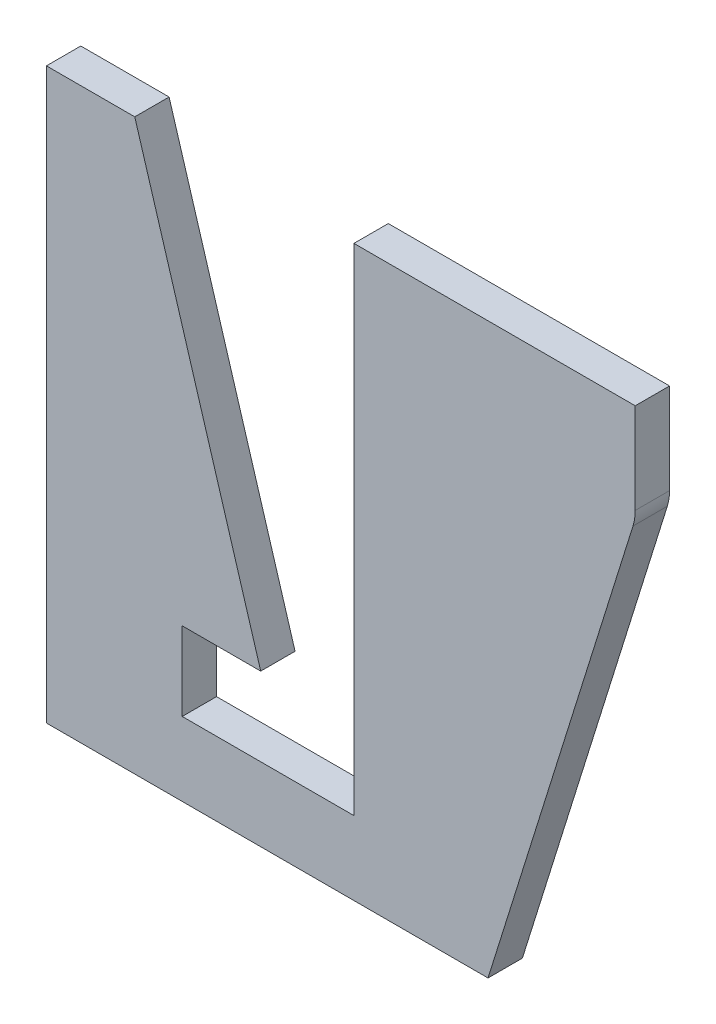
SolidWorks part; units mm, degrees
ref_plane "前视基准面" through (0, 0, 0) normal (0, 0, 1) x (1, 0, 0)
ref_plane "上视基准面" through (0, 0, 0) normal (0, 1, 0) x (1, 0, 0)
ref_plane "右视基准面" through (0, 0, 0) normal (1, 0, 0) x (0, 0, -1)
sketch "草图1" plane through (0, 0, 0) normal (0, 0, 1) x (1, 0, 0)
  line L0 (-79.4884, 60.8137) -> (-61.4884, 60.8137)
  line L1 (-61.4884, 60.8137) -> (-35.8163, -24.1863)
  line L2 (-35.8163, -24.1863) -> (-51.8163, -24.1863)
  line L3 (-51.8163, -24.1863) -> (-51.8163, -40.1863)
  line L4 (-51.8163, -40.1863) -> (-16.8163, -40.1863)
  line L5 (-16.8163, -40.1863) -> (-16.8163, 60.8137)
  line L6 (-16.8163, 60.8137) -> (40.5116, 60.8137)
  line L7 (40.5116, 60.8137) -> (40.5116, 40.8137)
  line L8 (40.5116, 40.8137) -> (10.5116, -55.1863)
  line L9 (10.5116, -55.1863) -> (-79.4884, -55.1863)
  line L10 (-79.4884, -55.1863) -> (-79.4884, 60.8137)
  dimension "D1" = 16
  dimension "D2" = 16
  dimension "D3" = 35
  dimension "D4" = 85
  dimension "D5" = 18
  dimension "D6" = 120
  dimension "D7" = 20
  dimension "D8" = 15
  dimension "D9" = 90
extrude "凸台-拉伸1" add sketch "草图1" along normal blind 7
fillet "圆角1" radius 10 1 edges at (40.5116, 40.8137, 3.5)
